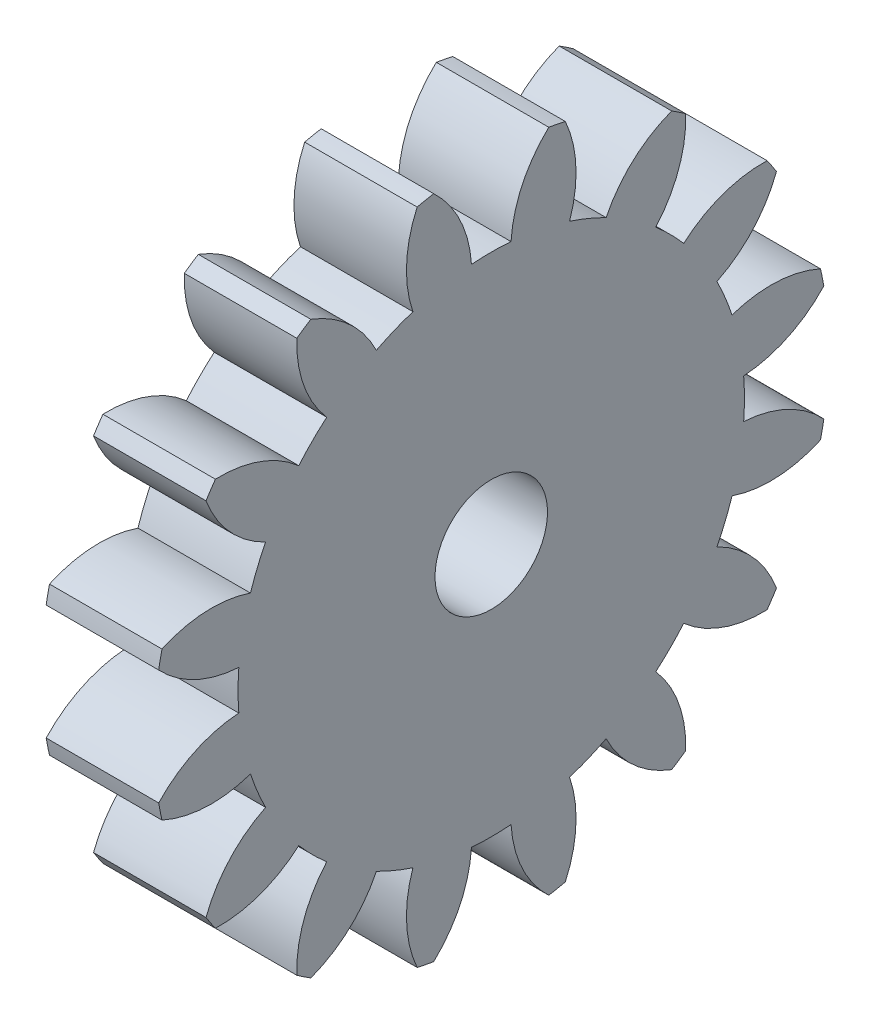
SolidWorks part; units mm, degrees
ref_plane "Plane1" through (0, 0, 0) normal (0, 0, 1) x (1, 0, 0)
ref_plane "Plane2" through (0, 0, 0) normal (0, 1, 0) x (1, 0, 0)
ref_plane "Plane3" through (0, 0, 0) normal (1, 0, 0) x (0, 0, -1)
sketch "HoldingSke" plane through (0, 0, 0) normal (0, 1, 0) x (1, 0, 0)
  line L0 (0, 0) -> (585.9851, -168.0285)
  line L1 (-15, 0) -> (100, 0) construction
  line L2 (0, 0) -> (-2.1039, 2.3779)
  line L3 (0, 0) -> (-11.863, 4.5341)
  line L4 (0, 0) -> (8.3015, 2.3804)
  line L5 (0, 0) -> (-5.9497, -2.219)
  line L6 (0, 0) -> (-2.632, -1.7758)
  line L7 (-2.1039, 2.3779) -> (-0.737, 8.5791)
  line L8 (-76.2, 54.61) -> (-72.771, 54.61)
  line L9 (-71.009, 38.7566) -> (-53.1078, 45.2721)
  line L10 (-76.2, 71.12) -> (104.1128, 71.12)
  line L11 (0, 0) -> (-3.175, 0)
  line L12 (-76.2, 101.6) -> (-76.1573, 101.6)
  line L13 (24.9733, 27.94) -> (52.9518, 28.4284)
  line L14 (24.9733, 27.94) -> (25.0241, 27.9398)
  line L15 (24.9733, 27.94) -> (100.4021, 29.52)
  circle A0 centre (0, 0) radius 1.5875
  circle A1 centre (0, 0) radius 3.175
  circle A2 centre (0, 0) radius 3.175
  circle A3 centre (0, 0) radius 1.5875
  dimension "MHD" = 6.35
  dimension "Hub_dia" = 6.35
  dimension "Bore" = 3.175
  dimension "MBD" = 3.175
  dimension "Num_teeth" = 16
  dimension "Pitch_radius" = 180.3128
  dimension "Pitch" = 609.6
  dimension "Width" = 3.175
  dimension "Overall_len" = 6.35
  dimension "Show_teeth" = 16
  dimension "Thickness" = 3.175
  dimension "OAL" = 6.3501
  dimension "T_dim" = 3.429
  dimension "Ap" = 20
  dimension "H" = 19.05
  dimension "Backlash" = 0.0427
  dimension "Addendum_fac" = 1
  dimension "Dedendum_fac" = 1.2
  dimension "Clearance_fac" = 0.2
  dimension "Dedendum_add" = 0.0508
sketch "BasProSke" plane through (0, 0, 0) normal (0, 1, 0) x (1, 0, 0)
  line L0 (-10, 0) -> (60, 0) construction
  line L1 (0, 0) -> (0, 9.525)
  line L2 (0, 0) -> (3.175, 0)
  line L3 (3.175, 0) -> (3.175, 9.525)
  line L4 (3.175, 9.525) -> (0, 9.525)
  dimension "Diameter" = 19.05
  dimension "Thickness" = 3.175
revolve "Base-Revolve" add sketch "BasProSke" angle 360 about L0
sketch "TooCutSke" plane through (0, 0, 0) normal (1, 0, 0) x (0, 0, -1)
  line L1 (0, 0) -> (0, 107) construction
  line L2 (0, 0) -> (-0.9045, 8.4182) construction
  line L3 (0, 0) -> (-3.2904, 16.5418) construction
  line L4 (-0.9045, 8.4182) -> (-1.6452, 8.2709) construction
  arc A0 (0.5582, 7.124) -> (-0.5582, 7.124) centre (0, 0) ccw
  arc A1 (1.6474, 9.4072) -> (-1.6474, 9.4072) centre (0, 0) ccw
  circle A2 centre (0, 0) radius 8.4667 construction
  circle A3 centre (0, 0) radius 7.9561 construction
  arc A4 (-0.5582, 7.124) -> (-1.6474, 9.4072) centre (-3.9383, 6.913) ccw
  arc A5 (1.6474, 9.4072) -> (0.5582, 7.124) centre (3.9383, 6.913) ccw
  dimension "Root_dia" = 14.2917
  dimension "Overcut_dia" = 19.1008
  dimension "Pitch_dia" = 16.9333
  dimension "Base_dia" = 15.9121
  dimension "Flank_rad" = 3.3867
  dimension "Half_ang" = 11.25
  dimension "Half_CT" = 0.7552
extrude "ToothCut" cut sketch "TooCutSke" along normal through all
fillet "Breaks" [suppressed] radius 0.0212
fillet "RootFillets" [suppressed] radius 0.2625
pattern_circular "TeethCuts" count 16 every 22.5 about axis through (-10, 0, 0) along (1, 0, 0) of "ToothCut", "RootFillets", "Breaks"
sketch "HubNeaOneSke" plane through (0, 0, 0) normal (-1, 0, 0) x (0, 0, 1)
  circle A0 centre (0, 0) radius 3.175
  dimension "Diameter" = 6.35
extrude "HubNearOne" [suppressed] add sketch "HubNeaOneSke" along normal blind 3.1751
sketch "HubNeaBotSke" plane through (0, 0, 0) normal (-1, 0, 0) x (0, 0, 1)
  circle A0 centre (0, 0) radius 3.175
  dimension "Diameter" = 6.35
extrude "HubNearBoth" [suppressed] add sketch "HubNeaBotSke" along normal blind 1.5875
ref_plane "FarPln" through (3.175, 0, 0) normal (1, 0, 0) x (0, 0, -1)
sketch "HubFarSke" plane through (3.175, 0, 0) normal (1, 0, 0) x (0, 0, -1)
  circle A0 centre (0, 0) radius 3.175
  dimension "Diameter" = 6.35
extrude "HubFar" [suppressed] add sketch "HubFarSke" along normal blind 1.5875
sketch "BorSke" plane through (0, 0, 0) normal (1, 0, 0) x (0, 0, -1)
  circle A0 centre (0, 0) radius 1.5875
  dimension "Diameter" = 3.175
extrude "Bore" cut sketch "BorSke" along normal mid plane 12.7001
sketch "KeySke" plane through (0, 0, 0) normal (1, 0, 0) x (0, 0, -1)
  line L0 (-0.127, 0) -> (-0.127, 1.8415)
  line L1 (-0.127, 1.8415) -> (0.127, 1.8415)
  line L2 (0.127, 1.8415) -> (0.127, 0)
  line L3 (0, 0) -> (0, 34) construction
  line L4 (-0.127, 0) -> (0.127, 0)
  dimension "Offset" = 1.8415
  dimension "Width" = 0.254
extrude "Keyway" [suppressed] cut sketch "KeySke" along normal mid plane 12.7001
pattern_circular "Keyway2" [suppressed] count 2 every 90 about axis through (-10, 0, 0) along (1, 0, 0)
equation "' \"Pitch@HoldingSke\" = 4"
equation "' \"Num_teeth@HoldingSke\" = 12"
equation "' \"Ap@HoldingSke\" =  20"
equation "' \"Width@HoldingSke\" = 0.5"
equation "' \"Hub_dia@HoldingSke\"= 1"
equation "' \"Overall_len@HoldingSke\" = 1.0"
equation "' \"Bore@HoldingSke\" = 0.75"
equation "' \"T_dim@HoldingSke\" = 0.85"
equation "' \"Width@KeySke\" = 0.25"
equation "' \"Show_teeth@HoldingSke\" = 13"
equation "' \"Backlash@HoldingSke\" = 0.009"
equation "' \"Addendum_fac@HoldingSke\" = 1.0"
equation "' \"Dedendum_fac@HoldingSke\" = 1.25"
equation "' \"Dedendum_add@HoldingSke\" = 0.00005"
equation "' \"Clearance_fac@HoldingSke\" = 0.25"
equation "' \"Pitch@HoldingSke\" = 0.5"
equation "' \"Num_teeth@HoldingSke\" = 23"
equation "' \"Show_teeth@HoldingSke\" = 23"
equation "' \"Backlash@HoldingSke\" = 0.0375"
equation "\"Overcut_dia@TooCutSke\" = (\"Num_teeth@HoldingSke\" + 2 * \"Addendum_fac@HoldingSke\") / \"Pitch@HoldingSke\" + 0.002"
equation "\"Pitch_dia@TooCutSke\" = \"Num_teeth@HoldingSke\" / \"Pitch@HoldingSke\""
equation "\"Base_dia@TooCutSke\" = \"Num_teeth@HoldingSke\" / \"Pitch@HoldingSke\" * cos((\"Ap@HoldingSke\"  * 3.14159265 / 180))"
equation "\"Root_dia@TooCutSke\" = (\"Num_teeth@HoldingSke\" + 2) / \"Pitch@HoldingSke\" - 2 * (\"Addendum_fac@HoldingSke\" + \"Dedendum_fac@HoldingSke\") / \"Pitch@HoldingSke\" - \"Dedendum_add@HoldingSke\" * 2"
equation "\"Half_ang@TooCutSke\" = 180 / \"Num_teeth@HoldingSke\""
equation "\"Half_CT@TooCutSke\" = \"Num_teeth@HoldingSke\" / \"Pitch@HoldingSke\" * sin((3.14159265 / 2 / \"Num_teeth@HoldingSke\")) / 2 - 7 * \"Backlash@HoldingSke\" / 4"
equation "\"Flank_rad@TooCutSke\" = \"Num_teeth@HoldingSke\" / \"Pitch@HoldingSke\" / 5"
equation "\"Radius@RootFillets\" = \"Clearance_fac@HoldingSke\" / \"Pitch@HoldingSke\" + \"Dedendum_add@HoldingSke\""
equation "\"Break_rad@Breaks\" = 0.02 / \"Pitch@HoldingSke\""
equation "\"Thickness@HoldingSke\" = \"Width@HoldingSke\""
equation "\"OAL@HoldingSke\" = \"Thickness@HoldingSke\""
equation "\"MHD@HoldingSke\" = (\"Num_teeth@HoldingSke\" + 2) / \"Pitch@HoldingSke\" - 2 * (\"Addendum_fac@HoldingSke\" + \"Dedendum_fac@HoldingSke\")  / \"Pitch@HoldingSke\" - \"Dedendum_add@HoldingSke\" * 2"
equation "\"MBD@HoldingSke\" = (\"Num_teeth@HoldingSke\" + 2) / \"Pitch@HoldingSke\" - 2 * (\"Addendum_fac@HoldingSke\" + \"Dedendum_fac@HoldingSke\")  / \"Pitch@HoldingSke\" - \"Dedendum_add@HoldingSke\" * 2 - 0.002"
equation "\"MHD@HoldingSke\" = ((sgn( \"MHD@HoldingSke\" - \"Hub_dia@HoldingSke\" )-1)*( \"MHD@HoldingSke\" - \"Hub_dia@HoldingSke\" ))/-2+ \"Hub_dia@HoldingSke\""
equation "\"MBD@HoldingSke\" = ((sgn( \"MBD@HoldingSke\" - \"Bore@HoldingSke\" )-1)*( \"MBD@HoldingSke\" - \"Bore@HoldingSke\" ))/-2+ \"Bore@HoldingSke\""
equation "\"OAL@HoldingSke\" = ((sgn( \"OAL@HoldingSke\" - \"Overall_len@HoldingSke\" )+1)*( \"OAL@HoldingSke\" - \"Overall_len@HoldingSke\" ))/2 + \"Overall_len@HoldingSke\" + 0.000002"
equation "\"Num_teeth@TeethCuts\" = int( \"Show_teeth@HoldingSke\" ) + 1"
equation "\"Num_teeth@TeethCuts\" = ((sgn( \"Num_teeth@TeethCuts\" - \"Num_teeth@HoldingSke\" )-1)*( \"Num_teeth@TeethCuts\" - \"Num_teeth@HoldingSke\" ))/-2+ \"Num_teeth@HoldingSke\""
equation "\"Num_teeth@TeethCuts\" = ((sgn( \"Num_teeth@TeethCuts\" - 2.0)+1)*( \"Num_teeth@TeethCuts\" - 2.0))/2 +2.0"
equation "\"Angle@TeethCuts\" = 360.0 / \"Num_teeth@HoldingSke\""
equation "\"Diameter@BasProSke\" = (\"Num_teeth@HoldingSke\" + 2 * \"Addendum_fac@HoldingSke\") / \"Pitch@HoldingSke\""
equation "\"Thickness@BasProSke\"  = \"Thickness@HoldingSke\""
equation "' \"Fillet_rad@BasProSke\" =  \"Thickness@HoldingSke\" * 0.05"
equation "\"MHD@HoldingSke\" = ((sgn( \"MHD@HoldingSke\" - \"Root_dia@TooCutSke\" )-1)*( \"MHD@HoldingSke\" - \"Root_dia@TooCutSke\" ))/-2+ \"Root_dia@TooCutSke\""
equation "\"Diameter@HubNeaOneSke\" = \"MHD@HoldingSke\""
equation "\"Length@HubNearOne\" = \"OAL@HoldingSke\" - \"Thickness@BasProSke\""
equation "\"Diameter@HubNeaBotSke\" = \"MHD@HoldingSke\""
equation "\"Length@HubNearBoth\" = ( \"OAL@HoldingSke\" - \"Thickness@BasProSke\" ) / 2.0"
equation "\"Thickness@FarPln\" = \"Thickness@BasProSke\""
equation "\"Diameter@HubFarSke\" = \"MHD@HoldingSke\""
equation "\"Length@HubFar\" = ( \"OAL@HoldingSke\" - \"Thickness@BasProSke\" ) / 2.0"
equation "\"Diameter@BorSke\" = \"MBD@HoldingSke\""
equation "\"D1@Bore\" = \"OAL@HoldingSke\" * 2.0"
equation "\"D1@Keyway\" = \"OAL@HoldingSke\" * 2.0"
equation "\"Offset@KeySke\" = \"T_dim@HoldingSke\" - \"MBD@HoldingSke\" / 2.0"
